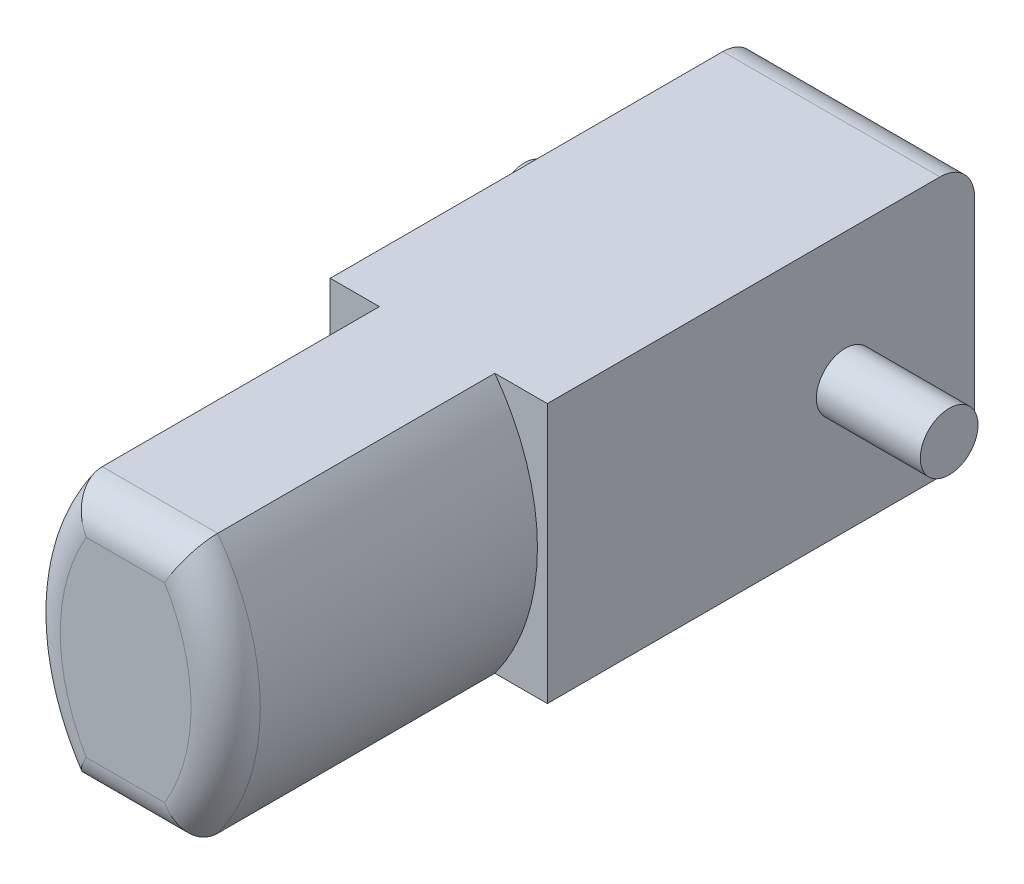
SolidWorks part; units mm, degrees
ref_plane "Front Plane" through (0, 0, 0) normal (0, 0, 1) x (1, 0, 0)
ref_plane "Top Plane" through (0, 0, 0) normal (0, 1, 0) x (1, 0, 0)
ref_plane "Right Plane" through (0, 0, 0) normal (1, 0, 0) x (0, 0, -1)
sketch "草图1" plane through (0, 0, 0) normal (0, 0, 1) x (1, 0, 0)
  line L1 (0, 0) -> (18.8, 0)
  line L2 (0, 0) -> (0, 22.5)
  line L3 (0, 22.5) -> (18.8, 22.5)
  line L4 (18.8, 0) -> (18.8, 22.5)
  dimension "D1" = 22.5
  dimension "D2" = 18.8
extrude "凸台-拉伸1" add sketch "草图1" along normal blind 37 contours L2 L1 L4 L3
fillet "圆角1" radius 3 2 edges at (9.4, 0, 0) (9.4, 22.5, 0)
sketch "草图2" plane through (0, 0, 37) normal (0, 0, 1) x (1, 0, 0)
  line L0 (9.2556, 24.4524) -> (9.2556, -4.423) construction
  line L1 (0, 22.5) -> (18.8, 22.5) construction
  line L2 (4.2556, 22.5) -> (14.2556, 22.5)
  line L3 (4.2556, 22.5) -> (4.2556, 0)
  line L4 (4.2556, 0) -> (14.2556, 0)
  line L5 (14.2556, 22.5) -> (14.2556, 0)
  line L6 (0, 0) -> (18.8, 0) construction
  line L7 (18.8, 0) -> (18.8, 22.5) construction
  line L8 (0, 0) -> (0, 22.5) construction
  arc A0 (4.2556, 22.5) -> (4.2556, 0) centre (19.8649, 11.25) ccw
  arc A1 (14.2556, 0) -> (14.2556, 22.5) centre (-1.06, 11.25) ccw
  line M5 (18.8, 22.5) -> (0, 22.5)
  line M7 (0, 0) -> (18.8, 0)
  dimension "D4" = 1.06
  dimension "D1" = 5
  dimension "D2" = 5
  dimension "D3" = 1.0649
extrude "凸台-拉伸2" add sketch "草图2" along normal blind 27 contours L0 L2 L3 M7 | L0 L4 L5 M5 | L5 A1 | L3 A0
fillet "圆角2" radius 3 4 edges at (0.624, 11.25, 64) (9.2556, 22.5, 64) (17.9434, 11.25, 64) (9.2556, 0, 64)
sketch "草图3" plane through (0, 0, 0) normal (-1, 0, 0) x (0, 0, 1)
  line L0 (0, 11.25) -> (68.3277, 11.25) construction
  line L1 (0, 3) -> (0, 19.5) construction
  circle A0 centre (11.2, 11.25) radius 2.5
  dimension "D2" = 5
  dimension "D1" = 11.2
extrude "凸台-拉伸3" add sketch "草图3" along normal blind 9 and the other way blind 27.8
